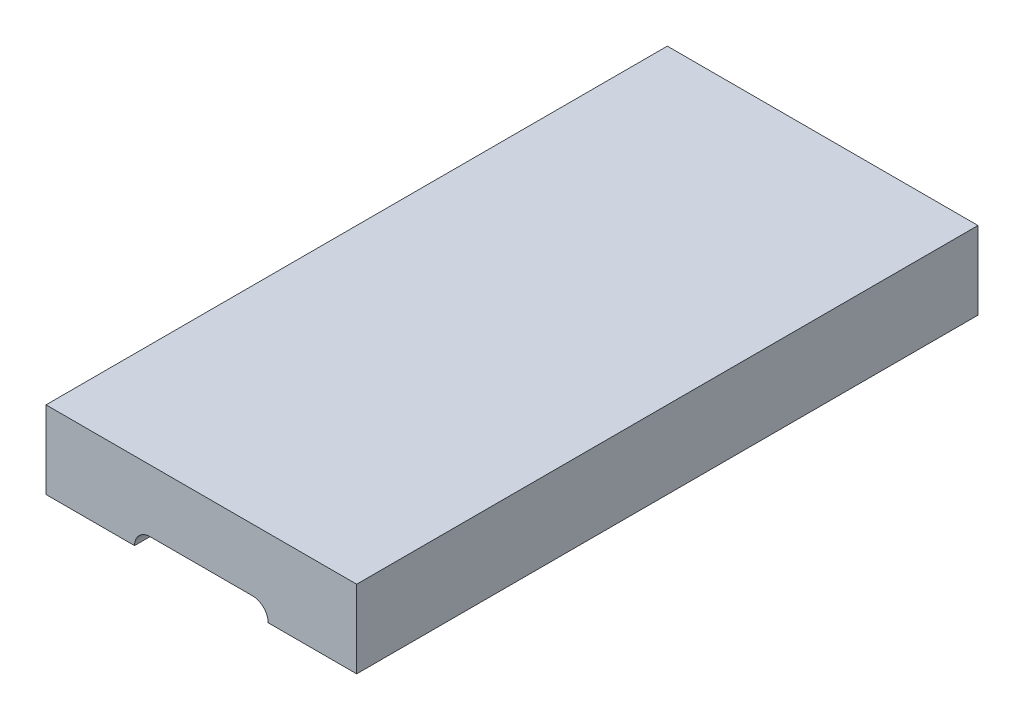
SolidWorks part; units mm, degrees
ref_plane "Front Plane" through (0, 0, 0) normal (0, 0, 1) x (1, 0, 0)
ref_plane "Top Plane" through (0, 0, 0) normal (0, 1, 0) x (1, 0, 0)
ref_plane "Right Plane" through (0, 0, 0) normal (1, 0, 0) x (0, 0, -1)
sketch "Sketch1" plane through (0, 0, 0) normal (0, 0, 1) x (1, 0, 0)
  line L1 (0, 0) -> (25.4, 0)
  line L2 (0, 0) -> (0, 12.7)
  line L3 (0, 12.7) -> (25.4, 12.7)
  line L4 (25.4, 0) -> (25.4, 12.7)
  dimension "D1" = 25.4
  dimension "D2" = 12.7
extrude "Boss-Extrude1" add sketch "Sketch1" against normal blind 50.8
sketch "Sketch2" plane through (0, 0, 0) normal (0, 0, 1) x (1, 0, 0)
  line L0 (8.509, 6.35) -> (16.891, 6.35) construction
  line L1 (8.509, 7.62) -> (16.891, 7.62)
  line L2 (8.509, 5.08) -> (16.891, 5.08)
  line L4 (0, 12.7) -> (0, 0) construction
  line L5 (0, 0) -> (25.4, 0) construction
  arc A0 (8.509, 7.62) -> (8.509, 5.08) centre (8.509, 6.35) ccw
  arc A1 (16.891, 5.08) -> (16.891, 7.62) centre (16.891, 6.35) ccw
  point P2 (12.7, 6.35)
  dimension "D1" = 8.382
  dimension "D2" = 2.54
  dimension "D3" = 6.35
  dimension "D4" = 12.7
extrude "Cut-Extrude1" cut sketch "Sketch2" against normal blind 50.8 contours L2 A1 L1 A0
sketch "Sketch3" plane through (25.4, 0, 0) normal (1, 0, 0) x (0, 0, -1)
  line L0 (50.8, 0) -> (50.8, 12.7) construction
  line L1 (0, 0) -> (50.8, 0)
  line L2 (0, 0) -> (0, 6.35)
  line L3 (0, 6.35) -> (50.8, 6.35)
  line L4 (50.8, 0) -> (50.8, 6.35)
  dimension "D1" = 6.35
extrude "Cut-Extrude3" cut sketch "Sketch3" against normal through all
sketch "Sketch5" plane through (0, 7.62, 0) normal (0, -1, 0) x (1, 0, 0)
  line L0 (18.161, -50.8) -> (25.4, -50.8) construction
  line L1 (2.54, -2.54) -> (22.86, -2.54)
  line L2 (2.54, -2.54) -> (2.54, -48.26)
  line L3 (2.54, -48.26) -> (22.86, -48.26)
  line L4 (22.86, -2.54) -> (22.86, -48.26)
  line L5 (0, -50.8) -> (0, 0) construction
  dimension "D1" = 45.72
  dimension "D2" = 2.54
  dimension "D3" = 20.32
  dimension "D4" = 2.54
extrude "Cut-Extrude4" cut sketch "Sketch5" against normal blind 3.81
